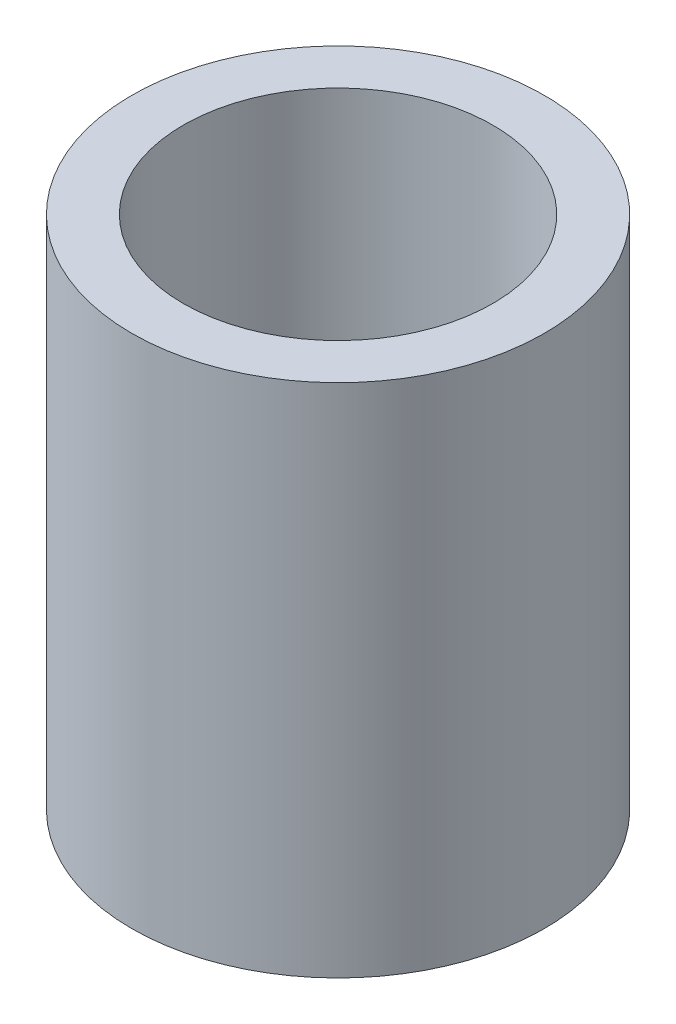
SolidWorks part; units mm, degrees
material "PPE"
ref_plane "Front Plane" through (0, 0, 0) normal (0, 0, 1) x (1, 0, 0)
ref_plane "Top Plane" through (0, 0, 0) normal (0, 1, 0) x (1, 0, 0)
ref_plane "Right Plane" through (0, 0, 0) normal (1, 0, 0) x (0, 0, -1)
sketch "Sketch1" plane through (0, 0, 0) normal (0, 1, 0) x (1, 0, 0)
  circle A0 centre (0, 0) radius 6.35
  dimension "D1" = 12.7
extrude "Boss-Extrude1" add sketch "Sketch1" along normal blind 15.875 contours A0
sketch "Sketch2" plane through (0, 15.875, 0) normal (0, 1, 0) x (1, 0, 0)
  circle A0 centre (0, 0) radius 4.7625
  dimension "D1" = 9.525
extrude "Cut-Extrude1" cut sketch "Sketch2" against normal through all contours A0
